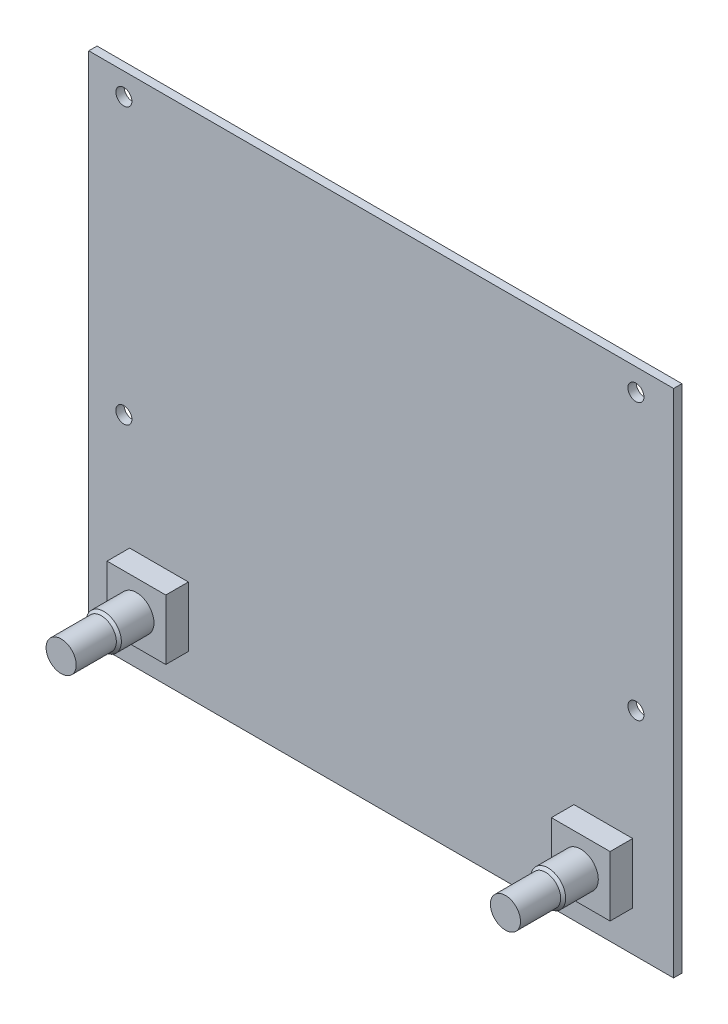
SolidWorks part; units mm, degrees
ref_plane "Front Plane" through (0, 0, 0) normal (0, 0, 1) x (1, 0, 0)
ref_plane "Top Plane" through (0, 0, 0) normal (0, 1, 0) x (1, 0, 0)
ref_plane "Right Plane" through (0, 0, 0) normal (1, 0, 0) x (0, 0, -1)
sketch "Sketch1" plane through (0, 0, 0) normal (0, 0, 1) x (1, 0, 0)
  line L1 (-58.2701, 50.8698) -> (58.2701, 50.8698)
  line L2 (-58.2701, 50.8698) -> (-58.2701, -50.8698)
  line L3 (-58.2701, -50.8698) -> (58.2701, -50.8698)
  line L4 (58.2701, 50.8698) -> (58.2701, -50.8698)
  line L5 (-58.2701, 50.8698) -> (58.2701, -50.8698) construction
  line L6 (-58.2701, -50.8698) -> (58.2701, 50.8698) construction
  circle A0 centre (-51.2699, 46.4502) radius 1.6002
  circle A1 centre (50.7695, 46.4502) radius 1.6002
  circle A2 centre (50.7695, -8.4493) radius 1.6002
  circle A3 centre (-51.2699, -8.4493) radius 1.6002
  point P0 (0, 0)
  dimension "D3" = 3.2004
  dimension "D6" = 3.2004
  dimension "D7" = 3.2004
  dimension "D8" = 3.2004
  dimension "D1" = 101.7397
  dimension "D2" = 116.5403
  dimension "D4" = 7.0002
  dimension "D5" = 4.4196
  dimension "D9" = 7.5006
  dimension "D10" = 54.8996
extrude "Boss-Extrude1" add sketch "Sketch1" along normal blind 1.6561
sketch "Sketch2" plane through (0, 0, 1.6561) normal (0, 0, 1) x (1, 0, 0)
  line L0 (0, 50.8698) -> (0, -50.8698) construction
  line L1 (-50.1193, -42.8688) -> (-38.42, -42.8688)
  line L2 (-50.1193, -42.8688) -> (-50.1193, -30.8699)
  line L3 (-50.1193, -30.8699) -> (-38.42, -30.8699)
  line L4 (-38.42, -42.8688) -> (-38.42, -30.8699)
  line L5 (58.2701, 50.8698) -> (-58.2701, 50.8698) construction
  line L36 (-58.2701, -50.8698) -> (58.2701, -50.8698) construction
  line L37 (50.1193, -30.8699) -> (38.42, -30.8699)
  line L38 (38.42, -42.8688) -> (38.42, -30.8699)
  line L39 (50.1193, -42.8688) -> (38.42, -42.8688)
  line L40 (50.1193, -42.8688) -> (50.1193, -30.8699)
  dimension "D1" = 8.1509
  dimension "D2" = 8.001
  dimension "D3" = 11.6992
  dimension "D4" = 11.999
  dimension "D5" = 8.1509
  dimension "D6" = 8.001
  dimension "D7" = 11.6992
  dimension "D8" = 11.999
extrude "Boss-Extrude2" add sketch "Sketch2" along normal blind 4.5
sketch "Sketch3" plane through (0, 0, 6.1561) normal (0, 0, 1) x (1, 0, 0)
  line L0 (-44.2697, -42.8688) -> (-44.2697, -30.8699) construction
  line L1 (-50.1193, -42.8688) -> (-38.42, -42.8688) construction
  line L2 (-38.42, -30.8699) -> (-50.1193, -30.8699) construction
  line L3 (-50.1193, -36.8694) -> (-38.42, -36.8694) construction
  line L4 (-50.1193, -30.8699) -> (-50.1193, -42.8688) construction
  line L5 (-38.42, -42.8688) -> (-38.42, -30.8699) construction
  line L6 (38.42, -42.8688) -> (50.1193, -30.8699) construction
  line L7 (50.1193, -42.8688) -> (38.42, -30.8699) construction
  circle A0 centre (-44.2697, -36.8694) radius 3.5
  circle A1 centre (44.2697, -36.8694) radius 3.5
  point P16 (-44.2697, -36.8694)
  point P26 (44.2697, -36.8694)
  dimension "D1" = 7
  dimension "D2" = 7
extrude "Boss-Extrude3" add sketch "Sketch3" along normal blind 7
chamfer "Chamfer1" distance 0.5 angle 45 2 edges at (-40.7697, -36.8694, 13.1561) (47.7697, -36.8694, 13.1561)
sketch "Sketch5" plane through (0, 0, 13.1561) normal (0, 0, 1) x (1, 0, 0)
  circle A0 centre (44.2697, -36.8694) radius 3 construction
  circle A1 centre (-44.2697, -36.8694) radius 3 construction
  circle A2 centre (44.2697, -36.8694) radius 3
  circle A3 centre (-44.2697, -36.8694) radius 3
extrude "Boss-Extrude4" add sketch "Sketch5" along normal blind 8
